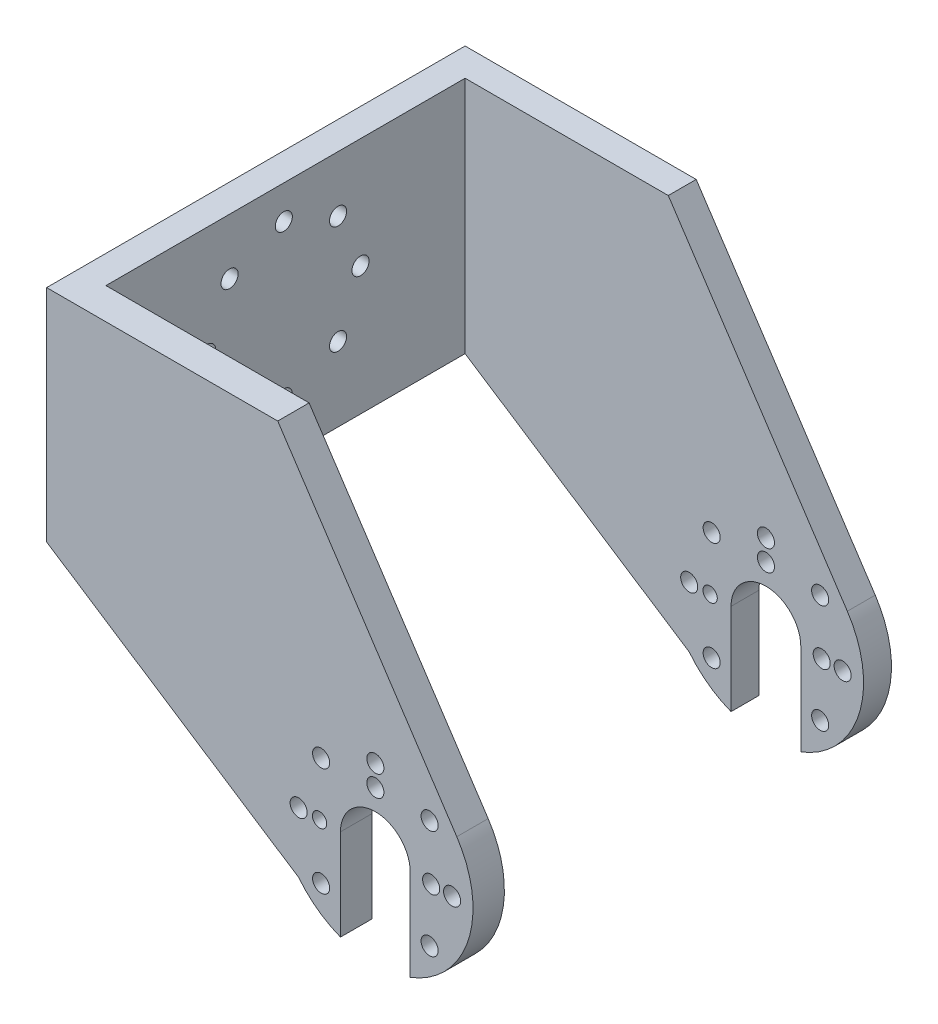
SolidWorks part; units mm, degrees
ref_plane "정면" through (0, 0, 0) normal (0, 0, 1) x (1, 0, 0)
ref_plane "윗면" through (0, 0, 0) normal (0, 1, 0) x (1, 0, 0)
ref_plane "우측면" through (0, 0, 0) normal (1, 0, 0) x (0, 0, -1)
sketch "스케치1" plane through (0, 0, 0) normal (0, 0, 1) x (1, 0, 0)
  line L0 (11.674, 7.7277) -> (-14, 46.5127)
  line L4 (-14, 46.5127) -> (-47.1329, 46.5127)
  line L5 (-11, -8.6603) -> (-47.1329, 14.9217)
  line L8 (-47.1329, 46.5127) -> (-47.1329, 14.9217)
  circle A18 centre (0, 0) radius 5
  circle A19 centre (0, 8) radius 1.225
  circle A20 centre (0, 11) radius 1.225
  arc A21 (-11, -8.6603) -> (11.674, 7.7277) centre (0, 0) ccw
  circle A22 centre (7.7782, 7.7782) radius 1.225
  circle A23 centre (8, 0) radius 1.225
  circle A24 centre (11, 0) radius 1.225
  circle A25 centre (7.7782, -7.7782) radius 1.225
  circle A26 centre (0, -8) radius 1.225
  circle A27 centre (0, -11) radius 1.225
  circle A28 centre (-7.7782, -7.7782) radius 1.225
  circle A29 centre (-8, 0) radius 1.025
  circle A30 centre (-11, 0) radius 1.225
  circle A31 centre (-7.7782, 7.7782) radius 1.225
  dimension "D1" = 10
  dimension "D3" = 2.45
  dimension "D5" = 28
  dimension "D6" = 2.05
  dimension "D2" = 8
  dimension "D4" = 11
  dimension "D7" = 7.7782
  dimension "D8" = 8
  dimension "D9" = 11
  dimension "D10" = 11.674
  dimension "D11" = 7.7782
  dimension "D12" = 8
  dimension "D13" = 14
  dimension "D14" = 47.1329
  dimension "D15" = 7.7782
  dimension "D16" = 11
  dimension "D17" = 14.9217
  dimension "D18" = 7.7782
  dimension "D19" = 8
  dimension "D20" = 11
extrude "보스-돌출1" add sketch "스케치1" along normal blind 60
sketch "스케치2" plane through (0, 46.5127, 0) normal (0, 1, 0) x (1, 0, 0)
  line L0 (-43.1329, -4) -> (14, -4)
  line L1 (14, -60) -> (14, 0) construction
  line L2 (14, -4) -> (14, -55.5)
  line L3 (14, -55.5) -> (-43.1329, -55.5)
  line L4 (-43.1329, -55.5) -> (-43.1329, -4)
  line L5 (-14, 0) -> (-47.1329, 0) construction
  line L6 (-47.1329, -60) -> (-47.1329, 0) construction
  point P4 (-30.5665, 0)
  dimension "D1" = 4
  dimension "D2" = 51.5
  dimension "D3" = 4
extrude "컷-돌출1" cut sketch "스케치2" against normal blind 66
sketch "스케치4" plane through (0, 0, 60) normal (0, 0, 1) x (1, 0, 0)
  line L0 (0, 5) -> (0, -5) construction
  line L1 (5, 0) -> (-5, 0) construction
  line L2 (-5, 0) -> (-5, -13.0767)
  line L3 (5, 0) -> (5, -13.0767)
  line L4 (-5, 0) -> (5, 0)
  circle A0 centre (0, 0) radius 5 construction
  arc A1 (-11, -8.6603) -> (11.674, 7.7277) centre (0, 0) ccw construction
  arc A2 (-5, -13.0767) -> (5, -13.0767) centre (0, 0) ccw
extrude "컷-돌출3" cut sketch "스케치4" against normal blind 60.339
sketch "스케치8" plane through (-47.1329, 0, 0) normal (-1, 0, 0) x (0, 0, 1)
  line L0 (0, 46.5127) -> (0, 14.9217) construction
  line L1 (60, 14.9217) -> (0, 14.9217) construction
  circle A11 centre (22.2171, 38.4973) radius 1.225
  circle A12 centre (29.9953, 41.7192) radius 1.225
  circle A13 centre (37.7734, 38.4973) radius 1.225
  circle A14 centre (40.9953, 30.7192) radius 1.225
  circle A15 centre (37.7734, 22.941) radius 1.225
  circle A16 centre (29.9953, 19.7192) radius 1.225
  circle A17 centre (22.2171, 22.941) radius 1.225
  circle A18 centre (18.9953, 30.7192) radius 1.225
  dimension "D1" = 2.45
  dimension "D2" = 18.9953
  dimension "D3" = 22.2171
  dimension "D4" = 29.9953
  dimension "D5" = 37.7734
  dimension "D6" = 40.9953
  dimension "D7" = 4.7975
  dimension "D8" = 8.0193
  dimension "D9" = 15.7975
  dimension "D10" = 23.5756
  dimension "D11" = 26.7975
extrude "컷-돌출4" cut sketch "스케치8" against normal blind 10
